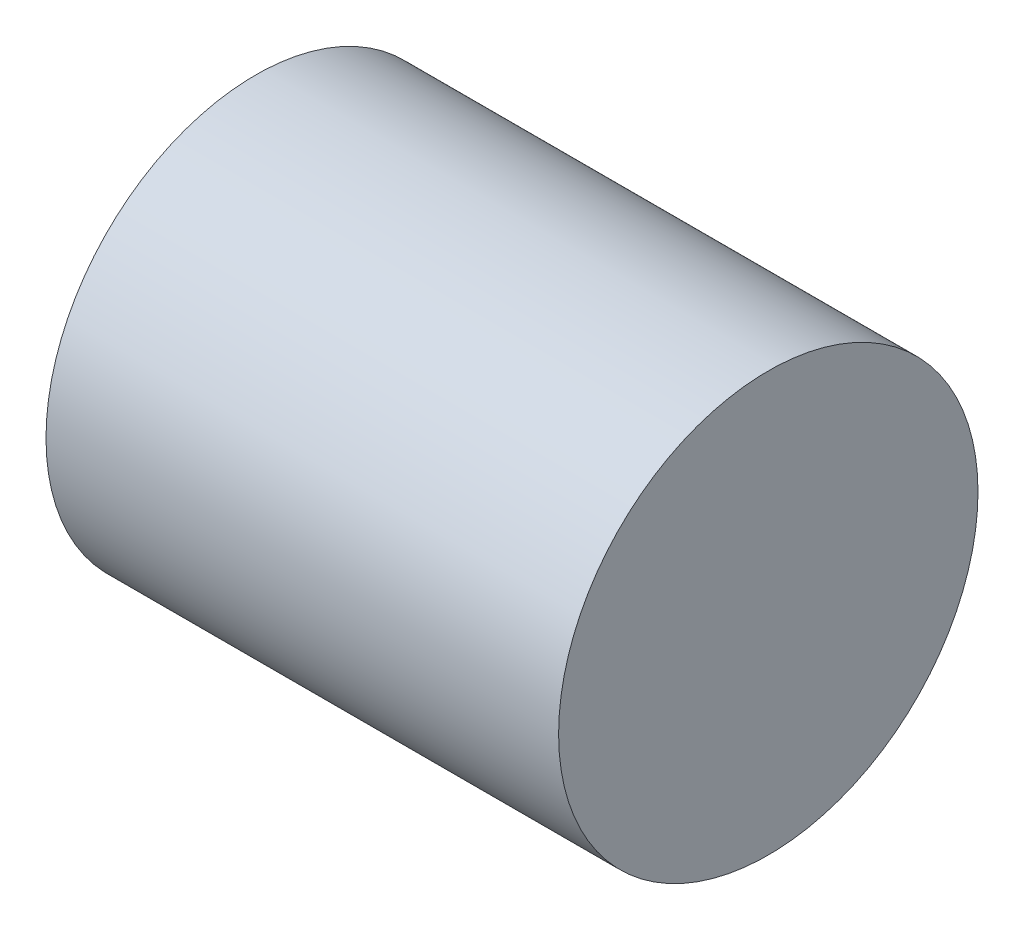
SolidWorks part; units mm, degrees
ref_plane "前视基准面" through (0, 0, 0) normal (0, 0, 1) x (1, 0, 0)
ref_plane "上视基准面" through (0, 0, 0) normal (0, 1, 0) x (1, 0, 0)
ref_plane "右视基准面" through (0, 0, 0) normal (1, 0, 0) x (0, 0, -1)
sketch "草图1" plane through (0, 0, 0) normal (1, 0, 0) x (0, 0, -1)
  circle A0 centre (-48.2889, 27.6229) radius 4.5
extrude "凸台-拉伸1" add sketch "草图1" along normal blind 11
